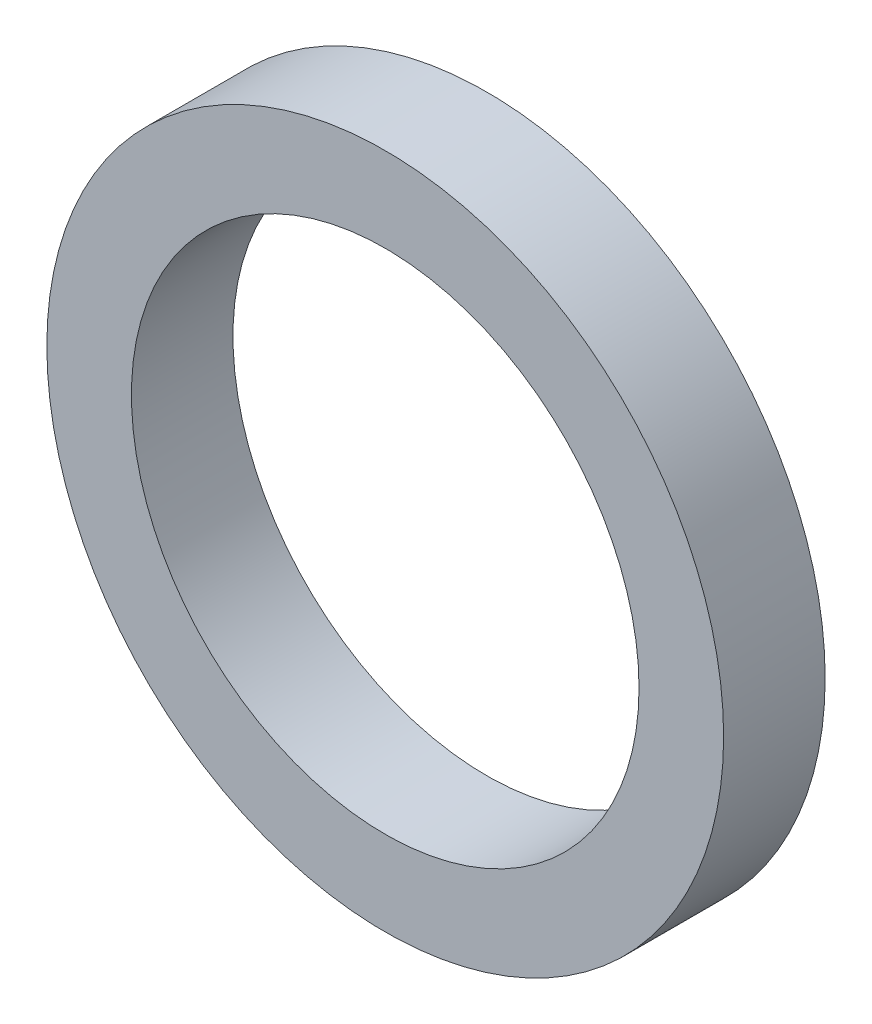
SolidWorks part; units mm, degrees
ref_plane "Plan de face" through (0, 0, 0) normal (0, 0, 1) x (1, 0, 0)
ref_plane "Plan de dessus" through (0, 0, 0) normal (0, 1, 0) x (1, 0, 0)
ref_plane "Plan de droite" through (0, 0, 0) normal (1, 0, 0) x (0, 0, -1)
sketch "Esquisse1" plane through (0, 0, 0) normal (0, 0, 1) x (1, 0, 0)
  circle A0 centre (0, 0) radius 20
  circle A1 centre (0, 0) radius 15
  dimension "D1" = 40
  dimension "D2" = 30
extrude "Extrusion1" add sketch "Esquisse1" along normal blind 6
